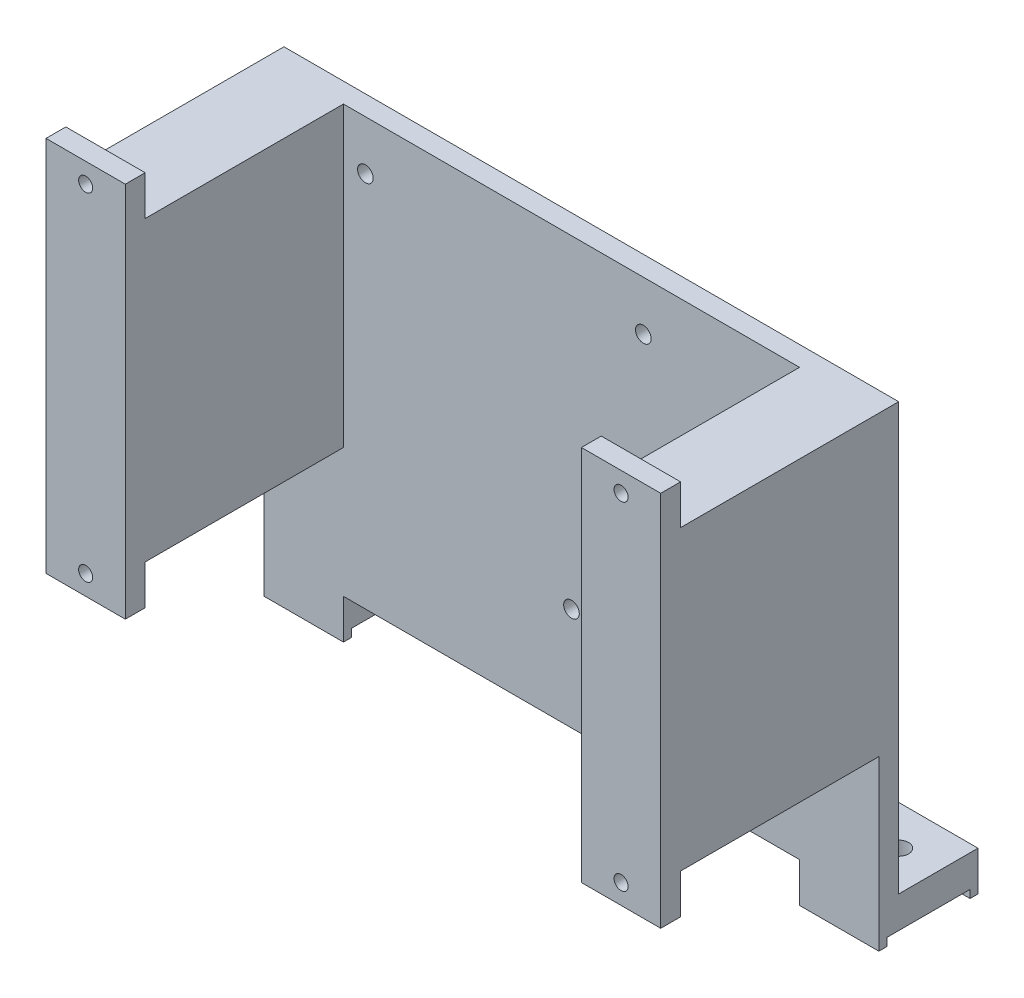
SolidWorks part; units mm, degrees
material "6061 Alloy"
ref_plane "Front Plane" through (0, 0, 0) normal (0, 0, 1) x (1, 0, 0)
ref_plane "Top Plane" through (0, 0, 0) normal (0, 1, 0) x (1, 0, 0)
ref_plane "Right Plane" through (0, 0, 0) normal (1, 0, 0) x (0, 0, -1)
sketch "Sketch1" plane through (0, 0, 0) normal (0, 1, 0) x (1, 0, 0)
  line L1 (-98.425, -41.275) -> (98.425, -41.275)
  line L2 (-98.425, -41.275) -> (-98.425, 41.275)
  line L3 (-98.425, 41.275) -> (98.425, 41.275)
  line L4 (98.425, -41.275) -> (98.425, 41.275)
  line L5 (-98.425, -41.275) -> (98.425, 41.275) construction
  line L6 (-98.425, 41.275) -> (98.425, -41.275) construction
  point P0 (0, 0)
  dimension "D1" = 82.55
  dimension "D2" = 196.85
extrude "Boss-Extrude1" add sketch "Sketch1" along normal blind 95.25
sketch "Sketch3" plane through (0, 95.25, 0) normal (0, 1, 0) x (1, 0, 0)
  line L0 (-98.425, -41.275) -> (98.425, -41.275) construction
  line L1 (-73.025, -41.275) -> (73.025, -41.275)
  line L2 (-73.025, -41.275) -> (-73.025, 34.925)
  line L3 (-73.025, 34.925) -> (73.025, 34.925)
  line L4 (73.025, -41.275) -> (73.025, 34.925)
  line L5 (-98.425, 41.275) -> (-98.425, -41.275) construction
  line L6 (98.425, -41.275) -> (98.425, 41.275) construction
  dimension "D1" = 76.2
  dimension "D2" = 25.4
  dimension "D3" = 25.4
extrude "Cut-Extrude1" cut sketch "Sketch3" against normal through all
sketch "Sketch4" plane through (0, 0, -41.275) normal (0, 0, -1) x (-1, 0, 0)
  line L1 (-98.425, 0) -> (-73.025, 0)
  line L2 (-98.425, 0) -> (-98.425, -53.975)
  line L3 (-98.425, -53.975) -> (-73.025, -53.975)
  line L4 (-73.025, 0) -> (-73.025, -53.975)
  dimension "D1" = 53.975
  dimension "D2" = 25.4
extrude "Boss-Extrude2" add sketch "Sketch4" against normal blind 6.35
sketch "Sketch5" plane through (0, 0, -41.275) normal (0, 0, -1) x (-1, 0, 0)
  line L0 (-73.025, -53.975) -> (-73.025, 0) construction
  line L1 (-98.425, -53.975) -> (-73.025, -53.975)
  line L2 (-98.425, -53.975) -> (-98.425, -41.275)
  line L3 (-98.425, -41.275) -> (-73.025, -41.275)
  line L4 (-73.025, -53.975) -> (-73.025, -41.275)
  dimension "D1" = 12.7
extrude "Boss-Extrude3" add sketch "Sketch5" along normal blind 25.4
sketch "Sketch6" plane through (98.425, 0, 0) normal (1, 0, 0) x (0, 0, -1)
  line L0 (34.925, -53.975) -> (66.675, -53.975) construction
  line L1 (37.465, -53.975) -> (64.135, -53.975)
  line L2 (37.465, -53.975) -> (37.465, -51.435)
  line L3 (37.465, -51.435) -> (64.135, -51.435)
  line L4 (64.135, -53.975) -> (64.135, -51.435)
  line L5 (34.925, 0) -> (34.925, -53.975) construction
  line L6 (66.675, -41.275) -> (66.675, -53.975) construction
  dimension "D1" = 2.54
  dimension "D2" = 2.54
  dimension "D3" = 2.54
extrude "Cut-Extrude2" cut sketch "Sketch6" against normal through all
hole_wizard "1/4 (0.25) Diameter Hole1" positions "Sketch7" profile "Sketch8" hole size "1/4" standard "ANSI Inch" end condition through all
sketch "Sketch7" plane through (0, -41.275, 0) normal (0, 1, 0) x (1, 0, 0)
  line L0 (73.025, 66.675) -> (98.425, 66.675) construction
  line L1 (98.425, 66.675) -> (98.425, 41.275) construction
  point P0 (85.725, 53.975)
  dimension "D1" = 12.7
  dimension "D2" = 12.7
sketch "Sketch8" plane through (85.725, -41.275, -53.975) normal (1, 0, 0) x (0, 0, 1)
  line L0 (0, 0) -> (0, 12.7)
  line L1 (0, 12.7) -> (3.175, 12.7)
  line L2 (3.175, 12.7) -> (3.175, 0)
  line L5 (3.175, 0) -> (0, 0)
  line L11 (0, -6.35) -> (0, 107.95) construction
  dimension "Thru Hole Dia." = 6.35
  dimension "Thru Hole Depth" = 12.7
sketch "Sketch16" plane through (0, 95.25, 0) normal (0, 1, 0) x (1, 0, 0)
  line L0 (98.425, -41.275) -> (98.425, 41.275) construction
  line L1 (-98.425, -41.275) -> (98.425, -41.275)
  line L2 (-98.425, -41.275) -> (-98.425, -34.925)
  line L3 (-98.425, -34.925) -> (98.425, -34.925)
  line L4 (98.425, -41.275) -> (98.425, -34.925)
  dimension "D1" = 6.35
extrude "Cut-Extrude3" cut sketch "Sketch16" against normal through all
sketch "Sketch11" plane through (0, 0, 41.275) normal (0, 0, 1) x (1, 0, 0)
  line L0 (98.425, 0) -> (98.425, -53.975) construction
  line L1 (73.025, 95.25) -> (98.425, 95.25)
  line L2 (73.025, 95.25) -> (73.025, 107.95)
  line L3 (73.025, 107.95) -> (98.425, 107.95)
  line L4 (98.425, 95.25) -> (98.425, 107.95)
  line L5 (73.025, 0) -> (98.425, 0)
  line L6 (73.025, 0) -> (73.025, -12.7)
  line L7 (73.025, -12.7) -> (98.425, -12.7)
  line L8 (98.425, 0) -> (98.425, -12.7)
  dimension "D1" = 25.4
  dimension "D2" = 12.7
  dimension "D3" = 12.7
extrude "Boss-Extrude4" add sketch "Sketch11" against normal blind 6.35 from surface at -6.35 starting at face at (85.725, 47.625, 34.925)
hole_wizard "#8 Clearance Hole1" positions "Sketch12" profile "Sketch13" hole size "#8" standard "ANSI Inch"
sketch "Sketch12" plane through (0, 0, 41.275) normal (0, 0, 1) x (1, 0, 0)
  line L0 (98.425, 107.95) -> (73.025, 107.95) construction
  line L1 (73.025, -12.7) -> (73.025, 107.95) construction
  line L2 (73.025, -12.7) -> (98.425, -12.7) construction
  point P0 (85.725, 101.6)
  point P2 (85.725, -6.35)
  dimension "D1" = 6.35
  dimension "D2" = 12.7
  dimension "D3" = 12.7
  dimension "D4" = 6.35
sketch "Sketch13" plane through (85.725, 101.6, 41.275) normal (1, 0, 0) x (0, -1, 0)
  line L0 (0, 0) -> (0, 12.7)
  line L1 (0, 12.7) -> (2.2479, 12.7)
  line L2 (2.2479, 12.7) -> (2.2479, 0)
  line L5 (2.2479, 0) -> (0, 0)
  line L11 (0, -6.35) -> (0, 107.95) construction
  dimension "Thru Hole Dia." = 4.4958
  dimension "Thru Hole Depth" = 12.7
mirror "Mirror1" about plane through (0, 0, 0) normal (1, 0, 0) of "#8 Clearance Hole1", "Boss-Extrude4", "Boss-Extrude2", "1/4 (0.25) Diameter Hole1", "Cut-Extrude2", "Boss-Extrude3"
sketch "Sketch14" plane through (0, 0, -41.275) normal (0, 0, -1) x (-1, 0, 0)
  line L0 (73.025, -41.275) -> (73.025, 0) construction
  line L1 (-73.025, 0) -> (73.025, 0)
  line L2 (-73.025, 0) -> (-73.025, -41.275)
  line L3 (-73.025, -41.275) -> (73.025, -41.275)
  line L4 (73.025, 0) -> (73.025, -41.275)
  dimension "D1" = 41.275
extrude "Boss-Extrude5" add sketch "Sketch14" against normal blind 6.35
hole_wizard "M6x1.0 Tapped Hole1" positions "Sketch19" profile "Sketch18" tap size "M6x1.0" standard "ANSI Metric"
sketch "Sketch19" plane through (0, 0, -41.275) normal (0, 0, -1) x (-1, 0, 0)
  point P0 (-23, 79.4169)
  point P3 (66, 79.4169)
  point P6 (0, -8.3332)
  point P9 (0, 0)
  point P10 (0, 0)
  point P11 (0, 0)
cosmetic thread "Hole Thread1" parameters "D1"=6.35, "D2"=6
cosmetic thread "Hole Thread2" parameters "D1"=6.35, "D2"=6
cosmetic thread "Hole Thread3" parameters "D1"=6.35, "D2"=6
sketch "Sketch18" plane through (23, 79.4169, -41.275) normal (1, 0, 0) x (0, 1, 0)
  line L0 (0, 0) -> (0, 16.4882)
  line L1 (0, 16.4882) -> (2.5, 14.986)
  line L2 (2.5, 14.986) -> (2.5, 0)
  line L5 (2.5, 0) -> (0, 0)
  line L10 (0, 16.4882) -> (-2.5, 14.986) construction
  line L11 (0, -6.35) -> (0, 107.95) construction
  point P3 (0, 0)
  dimension "Tap Drill Dia." = 5
  dimension "Tap Drill Depth" = 14.986
  dimension "Drill Angle" = 118
